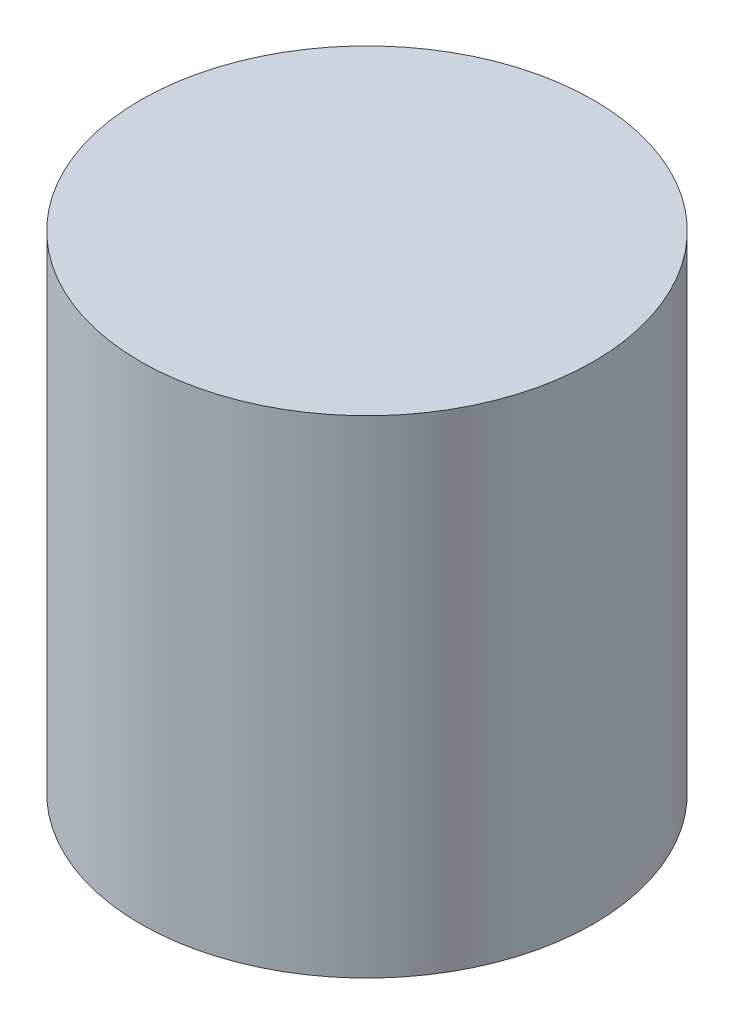
SolidWorks part; units mm, degrees
ref_plane "Front Plane" through (0, 0, 0) normal (0, 0, 1) x (1, 0, 0)
ref_plane "Top Plane" through (0, 0, 0) normal (0, 1, 0) x (1, 0, 0)
ref_plane "Right Plane" through (0, 0, 0) normal (1, 0, 0) x (0, 0, -1)
sketch "Sketch1" plane through (0, 0, 0) normal (0, 1, 0) x (1, 0, 0)
  circle A0 centre (0, 0) radius 10.16
  dimension "D1" = 20.32
extrude "Boss-Extrude1" add sketch "Sketch1" along normal blind 21.844
sketch "Sketch2" plane through (0, 21.844, 0) normal (0, 1, 0) x (1, 0, 0)
  line L0 (-10.16, 0) -> (10.16, 0)
  line L1 (-10.16, 0) -> (10.16, 0)
  circle A0 centre (0, 0) radius 10.16 construction
sketch "Sketch3" plane through (0, 0, 0) normal (0, -1, 0) x (1, 0, 0)
  line L0 (-10.16, 0) -> (10.16, 0)
